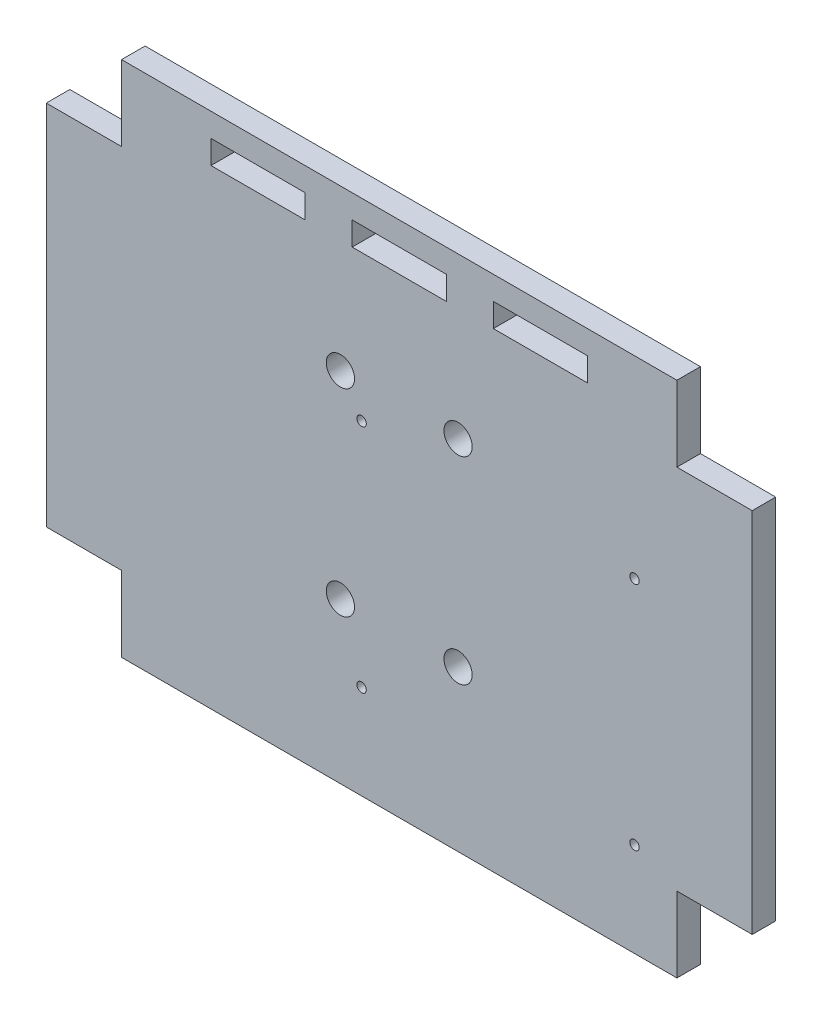
SolidWorks part; units mm, degrees
ref_plane "Plan de face" through (0, 0, 0) normal (0, 0, 1) x (1, 0, 0)
ref_plane "Plan de dessus" through (0, 0, 0) normal (0, 1, 0) x (1, 0, 0)
ref_plane "Plan de droite" through (0, 0, 0) normal (1, 0, 0) x (0, 0, -1)
sketch "Esquisse1" plane through (0, 0, 0) normal (0, 0, 1) x (1, 0, 0)
  line L1 (-34, 55) -> (84, 55)
  line L2 (-50, 39) -> (-50, -39)
  line L3 (-34, -55) -> (84, -55)
  line L4 (100, 39) -> (100, -39)
  line L7 (100, -39) -> (84, -39)
  line L8 (84, -55) -> (84, -39)
  line L11 (100, 39) -> (84, 39)
  line L12 (84, 55) -> (84, 39)
  line L15 (-50, -39) -> (-34, -39)
  line L16 (-34, -55) -> (-34, -39)
  line L19 (-50, 39) -> (-34, 39)
  line L20 (-34, 55) -> (-34, 39)
  dimension "D1" = 16
  dimension "D2" = 55
  dimension "D3" = 110
  dimension "D4" = 50
  dimension "D5" = 16
  dimension "D6" = 16
  dimension "D7" = 16
  dimension "D8" = 16
  dimension "D9" = 16
  dimension "D10" = 16
  dimension "D11" = 16
  dimension "D12" = 150
extrude "Boss.-Extru.1" add sketch "Esquisse1" against normal blind 5
sketch "Esquisse2" plane through (0, 0, -5) normal (0, 0, -1) x (-1, 0, 0)
  line L0 (34, -55) -> (-84, -55) construction
  line L1 (-100, -39) -> (-100, 39) construction
  circle A0 centre (-75, -35) radius 1
  circle A1 centre (-17, -35) radius 1
  circle A2 centre (-75, 14) radius 1
  circle A3 centre (-17, 14) radius 1
  dimension "D5" = 2
  dimension "D6" = 2
  dimension "D7" = 2
  dimension "D8" = 2
  dimension "D1" = 58
  dimension "D2" = 49
  dimension "D3" = 58
  dimension "D4" = 49
  dimension "D9" = 20
  dimension "D10" = 25
  dimension "D11" = 0
  dimension "D12" = 0
extrude "Enlèv. mat.-Extru.1" cut sketch "Esquisse2" against normal through all
sketch "Esquisse3" plane through (0, 0, -5) normal (0, 0, -1) x (-1, 0, 0)
  line L0 (-37.5, -21) -> (-12.5, 21) construction
  line L1 (-12.5, -21) -> (-37.5, 21) construction
  line L2 (34, -55) -> (-84, -55) construction
  line L3 (-100, -39) -> (-100, 39) construction
  circle A0 centre (-37.5, -21) radius 3
  circle A1 centre (-37.5, 21) radius 3
  circle A2 centre (-12.5, 21) radius 3
  circle A3 centre (-12.5, -21) radius 3
  point P8 (-25, 0)
  dimension "D4" = 6
  dimension "D5" = 6
  dimension "D6" = 6
  dimension "D7" = 6
  dimension "D1" = 42
  dimension "D2" = 0
  dimension "D3" = 25
  dimension "D8" = 55
  dimension "D9" = 75
  dimension "D10" = 0
  dimension "D11" = 25
  dimension "D12" = 42
extrude "Enlèv. mat.-Extru.2" cut sketch "Esquisse3" against normal through all
sketch "Esquisse4" plane through (0, 0, -5) normal (0, 0, -1) x (-1, 0, 0)
  line L0 (-84, 55) -> (34, 55) construction
  line L1 (-65, 45) -> (-45, 45)
  line L2 (-65, 45) -> (-65, 50)
  line L3 (-65, 50) -> (-45, 50)
  line L4 (-45, 45) -> (-45, 50)
  line L5 (-35, 45) -> (-15, 45)
  line L6 (-35, 45) -> (-35, 50)
  line L7 (-35, 50) -> (-15, 50)
  line L8 (-15, 45) -> (-15, 50)
  line L9 (-5, 45) -> (15, 45)
  line L10 (-5, 45) -> (-5, 50)
  line L11 (-5, 50) -> (15, 50)
  line L12 (15, 45) -> (15, 50)
  line L14 (-100, -39) -> (-100, 39) construction
  point P14 (-45, 47.5)
  point P15 (-25, 50)
  dimension "D1" = 20
  dimension "D2" = 5
  dimension "D3" = 5
  dimension "D4" = 5
  dimension "D5" = 20
  dimension "D6" = 20
  dimension "D7" = 5
  dimension "D8" = 5
  dimension "D9" = 5
  dimension "D10" = 10
  dimension "D11" = 10
  dimension "D12" = 75
extrude "Enlèv. mat.-Extru.3" cut sketch "Esquisse4" against normal through all
